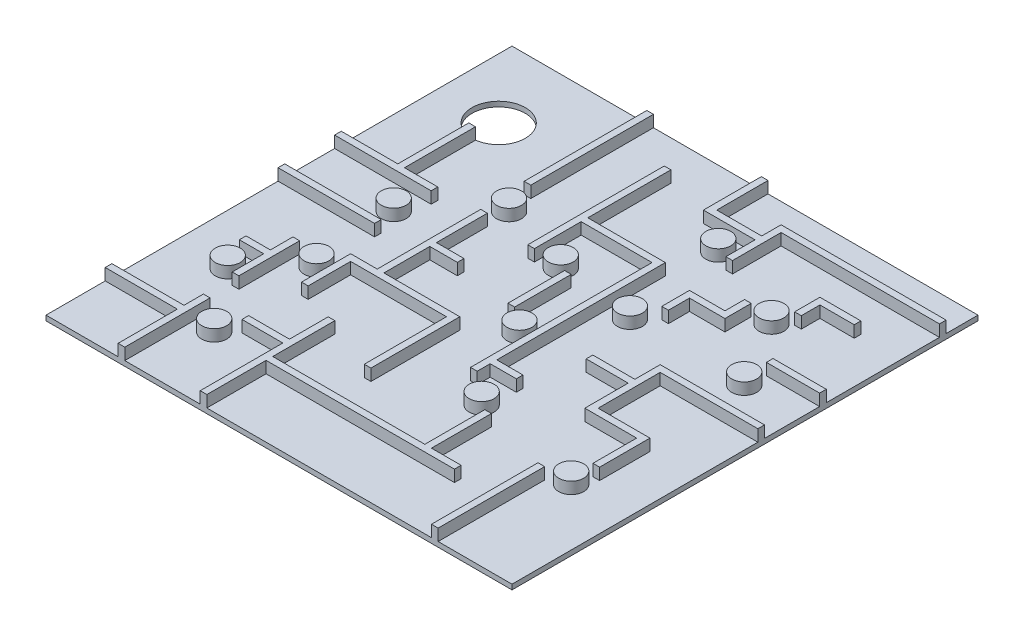
SolidWorks part; units mm, degrees
ref_plane "Front Plane" through (0, 0, 0) normal (0, 0, 1) x (1, 0, 0)
ref_plane "Top Plane" through (0, 0, 0) normal (0, 1, 0) x (1, 0, 0)
ref_plane "Right Plane" through (0, 0, 0) normal (1, 0, 0) x (0, 0, -1)
sketch "Sketch1" plane through (0, 0, 0) normal (0, 1, 0) x (1, 0, 0)
  line L1 (140, -140) -> (-140, -140)
  line L2 (140, -140) -> (140, 140)
  line L3 (140, 140) -> (-140, 140)
  line L4 (-140, -140) -> (-140, 140)
  line L5 (140, -140) -> (-140, 140) construction
  line L6 (140, 140) -> (-140, -140) construction
  circle A0 centre (-104, 96) radius 12.5 construction
  circle A2 centre (-104, 96) radius 16
  point P0 (0, 0)
  dimension "D2" = 25
  dimension "D4" = 36
  dimension "D5" = 44
  dimension "D3" = 32
  dimension "D1" = 280
extrude "Boss-Extrude1" add sketch "Sketch1" along normal mid plane 3
sketch "Sketch2" plane through (0, 1.5, 0) normal (0, 1, 0) x (1, 0, 0)
  line L0 (-139.5466, -22.5168) -> (140.7215, -22.5168) construction
  line L1 (-59, 140) -> (-59, 66.2868)
  line L5 (-140, 140) -> (-140, -140)
  line L6 (-140, -140) -> (140, -140)
  line L7 (140, -140) -> (140, 140)
  line L8 (140, 140) -> (-140, 140)
  line L9 (-140, 140) -> (-140, -140) construction
  line L10 (-140, -140) -> (140, -140) construction
  line L11 (140, -140) -> (140, 140) construction
  line L12 (140, 140) -> (-140, 140) construction
  line L14 (-82, 33.4008) -> (-82, 3.4233) construction
  line L22 (-59, 66.2868) -> (-55, 66.2868)
  line L25 (-55, 66.2868) -> (-55, 140)
  line L26 (-55, 140) -> (-59, 140)
  line L27 (-140, 37.4008) -> (-106, 37.4008)
  line L29 (-106, 37.4008) -> (-106, 80.1255)
  line L31 (-102, 37.4008) -> (-102, 80.1255)
  line L32 (-106, 37.4008) -> (-102, 80.1255) construction
  line L33 (-106, 80.1255) -> (-102, 37.4008) construction
  line L34 (-102, 37.4008) -> (-82, 37.4008)
  line L35 (-82, 37.4008) -> (-82, 33.4008)
  line L36 (-82, 33.4008) -> (-140, 33.4008)
  line L37 (-140, 33.4008) -> (-140, 37.4008)
  line L38 (-140, -100.4184) -> (-96.6685, -100.4184)
  line L39 (-140, 3.4233) -> (-82, 3.4233)
  line L40 (-140, 3.4233) -> (-140, -0.5767)
  line L41 (-140, -0.5767) -> (-82, -0.5767)
  line L42 (-82, 3.4233) -> (-82, -0.5767)
  line L43 (-96.6685, -100.4184) -> (-96.6685, -88.7386)
  line L44 (-96.6685, -88.7386) -> (-92.6685, -88.7386)
  line L45 (-92.6685, -88.7386) -> (-92.6685, -140)
  line L46 (-92.6685, -140) -> (-96.6685, -140)
  line L47 (-96.6685, -140) -> (-96.6685, -104.4184)
  line L48 (-96.6685, -104.4184) -> (-140, -104.4184)
  line L49 (-140, -104.4184) -> (-140, -100.4184)
  line L50 (-47.3451, -140) -> (-47.3451, -90.3646)
  line L51 (-47.3451, -90.3646) -> (-71.8819, -90.3646)
  line L52 (-71.8819, -90.3646) -> (-71.8819, -86.3646)
  line L53 (-71.8819, -86.3646) -> (-47.3451, -86.3646)
  line L54 (-47.3451, -86.3646) -> (-47.3451, -63.0886)
  line L55 (-47.3451, -63.0886) -> (-43.3451, -63.0886)
  line L56 (-43.3451, -63.0886) -> (-43.3451, -100.4184)
  line L57 (-43.3451, -100.4184) -> (48.0278, -100.4184)
  line L58 (48.0278, -100.4184) -> (48.0278, -64.3719)
  line L59 (48.0278, -64.3719) -> (52.0278, -64.3719)
  line L60 (52.0278, -64.3719) -> (52.0278, -100.4184)
  line L61 (52.0278, -100.4184) -> (69.8279, -100.4184)
  line L62 (69.8279, -100.4184) -> (69.8279, -104.4184)
  line L63 (69.8279, -104.4184) -> (-43.3451, -104.4184)
  line L64 (-43.3451, -104.4184) -> (-43.3451, -140)
  line L65 (-43.3451, -140) -> (-47.3451, -140)
  line L66 (140, 7.7373) -> (81.2931, 7.7373)
  line L67 (91.6226, -76) -> (95.6226, -76)
  line L68 (91.6226, -76) -> (91.6226, -140)
  line L69 (91.6226, -140) -> (95.6226, -140)
  line L70 (95.6226, -76) -> (95.6226, -140)
  line L71 (81.2931, 7.7373) -> (81.2931, -29.5435)
  line L72 (81.2931, -29.5435) -> (112.4312, -29.5435)
  line L73 (112.4312, -29.5435) -> (112.4312, -59.7773)
  line L74 (112.4312, -59.7773) -> (108.4312, -59.7773)
  line L75 (108.4312, -59.7773) -> (108.4312, -33.5435)
  line L76 (108.4312, -33.5435) -> (77.2931, -33.5435)
  line L77 (77.2931, -33.5435) -> (77.2931, -7.4768)
  line L78 (77.2931, -7.4768) -> (52.0278, -7.4768)
  line L79 (52.0278, -7.4768) -> (52.0278, -3.4768)
  line L80 (52.0278, -3.4768) -> (77.2931, -3.4768)
  line L81 (77.2931, -3.4768) -> (77.2931, 11.7373)
  line L82 (77.2931, 11.7373) -> (140, 11.7373)
  line L83 (140, 11.7373) -> (140, 7.7373)
  line L84 (-99.5107, -32.1119) -> (-95.5107, -32.1119)
  line L85 (140, 48.844) -> (108, 48.844)
  line L86 (140, 48.844) -> (140, 44.844)
  line L87 (140, 44.844) -> (108, 44.844)
  line L88 (108, 48.844) -> (108, 44.844)
  line L89 (-95.5107, -32.1119) -> (-95.5107, -68.5942)
  line L90 (-95.5107, -68.5942) -> (-99.5107, -68.5942)
  line L91 (-99.5107, -68.5942) -> (-99.5107, -49.6758)
  line L92 (-99.5107, -49.6758) -> (-114.1271, -49.6758)
  line L93 (-114.1271, -49.6758) -> (-114.1271, -45.6758)
  line L94 (-114.1271, -45.6758) -> (-99.5107, -45.6758)
  line L95 (-99.5107, -45.6758) -> (-99.5107, -32.1119)
  line L96 (-73.4352, -53.0425) -> (-69.4352, -53.0425)
  line L97 (-69.4352, -53.0425) -> (-69.4352, -27.5282)
  line L98 (-69.4352, -27.5282) -> (-11.8371, -27.5282)
  line L99 (-11.8371, -27.5282) -> (-11.8371, -76.9197)
  line L100 (-11.8371, -76.9197) -> (-7.8371, -76.9197)
  line L101 (-7.8371, -76.9197) -> (-7.8371, -23.5282)
  line L102 (-7.8371, -23.5282) -> (-53.4401, -23.5282)
  line L103 (-53.4401, -23.5282) -> (-53.4401, 4.0431)
  line L104 (-53.4401, 4.0431) -> (-36.8827, 4.0431)
  line L105 (-36.8827, 4.0431) -> (-36.8827, 8.0431)
  line L106 (-36.8827, 8.0431) -> (-53.4401, 8.0431)
  line L107 (-53.4401, 8.0431) -> (-53.4401, 38.6312)
  line L108 (-53.4401, 38.6312) -> (-57.4401, 38.6312)
  line L109 (-57.4401, 38.6312) -> (-57.4401, -23.5282)
  line L110 (-57.4401, -23.5282) -> (-73.4352, -23.5282)
  line L111 (-73.4352, -23.5282) -> (-73.4352, -53.0425)
  line L112 (114.8331, 94.8013) -> (114.8331, 90.8013)
  line L113 (-0.421, 32.0095) -> (3.579, 32.0095)
  line L114 (-0.421, 32.0095) -> (-0.421, -1.9905)
  line L115 (-0.421, -1.9905) -> (3.579, -1.9905)
  line L116 (3.579, 32.0095) -> (3.579, -1.9905)
  line L117 (114.8331, 90.8013) -> (94.2035, 90.8013)
  line L118 (94.2035, 90.8013) -> (94.2035, 79.6255)
  line L119 (94.2035, 79.6255) -> (90.2035, 79.6255)
  line L120 (90.2035, 79.6255) -> (90.2035, 94.8013)
  line L121 (90.2035, 94.8013) -> (114.8331, 94.8013)
  line L122 (68.7421, 71) -> (68.7421, 59.1986)
  line L123 (68.7421, 59.1986) -> (47.4471, 59.1986)
  line L124 (47.4471, 59.1986) -> (47.4471, 42.5547)
  line L125 (47.4471, 42.5547) -> (51.4471, 42.5547)
  line L126 (51.4471, 42.5547) -> (51.4471, 55.1986)
  line L127 (51.4471, 55.1986) -> (72.7421, 55.1986)
  line L128 (72.7421, 55.1986) -> (72.7421, 71)
  line L129 (72.7421, 71) -> (68.7421, 71)
  line L130 (21.7271, -46.6316) -> (25.7271, -46.6316)
  line L131 (25.7271, -46.6316) -> (25.7271, -38.8445)
  line L132 (25.7271, -38.8445) -> (41.4595, -38.8445)
  line L133 (41.4595, -38.8445) -> (41.4595, -34.8445)
  line L134 (41.4595, -34.8445) -> (25.7271, -34.8445)
  line L135 (25.7271, -34.8445) -> (25.7271, 66.4202)
  line L136 (25.7271, 66.4202) -> (-20.8726, 66.4202)
  line L137 (-20.8726, 66.4202) -> (-20.8726, 116.3442)
  line L138 (-20.8726, 116.3442) -> (-24.8726, 116.3442)
  line L139 (-24.8726, 116.3442) -> (-24.8726, 34.358)
  line L140 (-24.8726, 34.358) -> (-20.8726, 34.358)
  line L141 (-20.8726, 34.358) -> (-20.8726, 62.4202)
  line L142 (-20.8726, 62.4202) -> (21.7271, 62.4202)
  line L143 (21.7271, 62.4202) -> (21.7271, -46.6316)
  line L144 (140, 116.8451) -> (44.8417, 116.8451)
  line L145 (44.8417, 116.8451) -> (44.8417, 87.6566)
  line L146 (44.8417, 87.6566) -> (40.8417, 87.6566)
  line L147 (40.8417, 87.6566) -> (40.8417, 105.182)
  line L148 (40.8417, 105.182) -> (9.8488, 105.182)
  line L149 (9.8488, 105.182) -> (9.8488, 140)
  line L150 (9.8488, 140) -> (13.8488, 140)
  line L151 (13.8488, 140) -> (13.8488, 109.182)
  line L152 (13.8488, 109.182) -> (40.8417, 109.182)
  line L153 (40.8417, 109.182) -> (40.8417, 120.8451)
  line L154 (40.8417, 120.8451) -> (140, 120.8451)
  line L155 (140, 120.8451) -> (140, 116.8451)
  circle A0 centre (-104, 96) radius 16 construction
  circle A1 centre (-104, 96) radius 16 construction
  arc A5 (-102, 80.1255) -> (-106, 80.1255) centre (-104, 96) cw
  circle A6 centre (-54.759, 52.9828) radius 7.5
  circle A7 centre (-89.4735, 18.412) radius 7.5
  circle A8 centre (-83.7389, -33.6905) radius 7.5
  circle A9 centre (-109.5163, -61.2699) radius 7.5
  circle A10 centre (-80.6927, -98.2301) radius 7.5
  circle A12 centre (37.5874, -55.832) radius 7.5
  circle A13 centre (105.9105, -70.3332) radius 7.5
  circle A14 centre (11.8193, -7.3525) radius 7.5
  circle A15 centre (-9.7559, 39.067) radius 7.5
  circle A16 centre (29.1701, 94.8013) radius 7.5
  circle A17 centre (82.6249, 73.2846) radius 7.5
  circle A18 centre (37.5874, 33.2669) radius 7.5
  circle A19 centre (106.2527, 33.2879) radius 7.5
  point P9 (-82, 18.412)
  point P10 (0, 0)
  point P11 (0, 0)
  point P21 (-104, 58.7631)
  point P66 (93.6226, -76)
  dimension "D6" = 29
  dimension "D8" = 15
  dimension "D52" = 15
  dimension "D53" = 15
  dimension "D54" = 15
  dimension "D55" = 15
  dimension "D57" = 15
  dimension "D58" = 15
  dimension "D59" = 15
  dimension "D60" = 15
  dimension "D61" = 15
  dimension "D62" = 15
  dimension "D63" = 15
  dimension "D64" = 15
  dimension "D1" = 0
  dimension "D4" = 4
  dimension "D9" = 4
  dimension "D10" = 4
  dimension "D11" = 58
  dimension "D12" = 4
  dimension "D13" = 58
  dimension "D14" = 4
  dimension "D15" = 4
  dimension "D16" = 4
  dimension "D17" = 4
  dimension "D18" = 4
  dimension "D19" = 4
  dimension "D20" = 4
  dimension "D21" = 4
  dimension "D22" = 64
  dimension "D23" = 4
  dimension "D24" = 4
  dimension "D25" = 4
  dimension "D26" = 4
  dimension "D27" = 4
  dimension "D28" = 4
  dimension "D29" = 32
  dimension "D30" = 4
  dimension "D31" = 4
  dimension "D32" = 4
  dimension "D33" = 4
  dimension "D34" = 4
  dimension "D35" = 4
  dimension "D36" = 4
  dimension "D37" = 4
  dimension "D38" = 34
  dimension "D39" = 4
  dimension "D40" = 4
  dimension "D41" = 4
  dimension "D42" = 4
  dimension "D43" = 4
  dimension "D44" = 4
  dimension "D45" = 4
  dimension "D46" = 4
  dimension "D47" = 4
  dimension "D48" = 4
  dimension "D49" = 4
  dimension "D50" = 4
  dimension "D51" = 4
extrude "Boss-Extrude2" add sketch "Sketch2" along normal blind 7
sketch "Sketch4" plane through (0, 1.5, 0) normal (0, 1, 0) x (1, 0, 0)
  line L0 (-59, 140) -> (-140, 140) construction
  line L1 (-103.2689, 140) -> (-87.6691, 140)
  line L2 (-103.2689, 140) -> (-103.2689, 109.252)
  line L3 (-103.2689, 109.252) -> (-87.6691, 109.252)
  line L4 (-87.6691, 140) -> (-87.6691, 109.252)
  line L5 (5.9631, 143.7406) -> (7.9794, 102.774)
  line L6 (-145.5082, 88.7508) -> (-75.5684, 88.7508)
  line L7 (-145.5082, 88.7508) -> (-145.5082, 30.0852)
  line L8 (-145.5082, 30.0852) -> (-75.5684, 30.0852)
  line L9 (-75.5684, 88.7508) -> (-75.5684, 30.0852)
  line L10 (-62.1484, 143.7406) -> (-36.1488, 143.7406)
  line L11 (-62.1484, 143.7406) -> (-62.1484, 63.1419)
  line L12 (-62.1484, 63.1419) -> (-36.1488, 63.1419)
  line L13 (-36.1488, 143.7406) -> (-36.1488, 63.1419)
  line L14 (-147.4549, 7.7999) -> (-80.2273, 7.7999)
  line L15 (-147.4549, 7.7999) -> (-147.4549, -3.3428)
  line L16 (-147.4549, -3.3428) -> (-80.2273, -3.3428)
  line L17 (-80.2273, 7.7999) -> (-80.2273, -3.3428)
  line L18 (-147.4549, -83.9416) -> (-90.2557, -83.9416)
  line L19 (-147.4549, -83.9416) -> (-147.4549, -144.4835)
  line L20 (-147.4549, -144.4835) -> (-90.2557, -144.4835)
  line L21 (-90.2557, -83.9416) -> (-90.2557, -144.4835)
  line L22 (97.7216, -74.6829) -> (89.8032, -74.6829)
  line L23 (97.7216, -74.6829) -> (97.7216, -144.4835)
  line L24 (97.7216, -144.4835) -> (89.8032, -144.4835)
  line L25 (89.8032, -74.6829) -> (89.8032, -144.4835)
  line L26 (143.8995, -60.5264) -> (51.0585, -60.5264)
  line L27 (143.8995, -60.5264) -> (143.8995, 16.1793)
  line L28 (143.8995, 16.1793) -> (51.0585, 16.1793)
  line L29 (51.0585, -60.5264) -> (51.0585, 16.1793)
  line L30 (88.927, 78.8767) -> (116.5902, 78.8767)
  line L31 (88.927, 78.8767) -> (88.927, 97.3845)
  line L32 (88.927, 97.3845) -> (116.5902, 97.3845)
  line L33 (116.5902, 78.8767) -> (116.5902, 97.3845)
  line L34 (73.3744, 72.1075) -> (45.9857, 72.1075)
  line L35 (73.3744, 72.1075) -> (73.3744, 41.1619)
  line L36 (73.3744, 41.1619) -> (45.9857, 41.1619)
  line L37 (45.9857, 72.1075) -> (45.9857, 41.1619)
  line L38 (105.2092, 50.41) -> (142.3795, 50.41)
  line L39 (105.2092, 50.41) -> (105.2092, 43.6518)
  line L40 (105.2092, 43.6518) -> (142.3795, 43.6518)
  line L41 (142.3795, 50.41) -> (142.3795, 43.6518)
  line L42 (7.9794, 102.774) -> (36.2066, 102.774)
  line L43 (36.2066, 102.774) -> (36.2066, 85.384)
  line L44 (36.2066, 85.384) -> (47.7999, 85.384)
  line L45 (47.7999, 85.384) -> (47.7999, 114.3673)
  line L46 (47.7999, 114.3673) -> (142.3795, 114.3673)
  line L47 (142.3795, 114.3673) -> (142.3795, 146.3749)
  line L48 (142.3795, 146.3749) -> (5.9631, 143.7406)
  line L49 (45.9857, -63.0608) -> (55.6128, -63.0608)
  line L50 (55.6128, -63.0608) -> (55.6128, -94.5644)
  line L51 (55.6128, -94.5644) -> (73.3744, -98.5969)
  line L52 (73.3744, -98.5969) -> (71.3652, -107.4466)
  line L53 (71.3652, -107.4466) -> (-50.2392, -144.4835)
  line L54 (-50.2392, -144.4835) -> (-51.2032, -94.5644)
  line L55 (-51.2032, -94.5644) -> (-74.182, -91.5401)
  line L56 (-74.182, -91.5401) -> (-74.182, -83.9416)
  line L57 (-74.182, -83.9416) -> (-51.2032, -83.9416)
  line L58 (-51.2032, -83.9416) -> (-51.2032, -60.5264)
  line L59 (-51.2032, -60.5264) -> (-41.5994, -61.7904)
  line L60 (-41.5994, -61.7904) -> (-39.8871, -96.5806)
  line L61 (-39.8871, -96.5806) -> (42.0032, -96.5806)
  line L62 (42.0032, -96.5806) -> (45.9857, -63.0608)
  line L63 (-5.6302, -79.1855) -> (-16.4674, -79.1855)
  line L64 (-16.4674, -79.1855) -> (-16.4674, -32.0613)
  line L65 (-16.4674, -32.0613) -> (-66.3537, -32.0613)
  line L66 (-66.3537, -32.0613) -> (-66.3537, -52.7277)
  line L67 (-66.3537, -52.7277) -> (-69.4859, -55.8599)
  line L68 (-69.4859, -55.8599) -> (-74.182, -55.8599)
  line L69 (-74.182, -55.8599) -> (-74.182, -19.9639)
  line L70 (-74.182, -19.9639) -> (-60.8244, -19.9639)
  line L71 (-60.8244, -19.9639) -> (-60.8244, 41.1619)
  line L72 (-60.8244, 41.1619) -> (-50.7212, 41.1619)
  line L73 (-50.7212, 41.1619) -> (-5.6302, -25.2565)
  line L74 (-5.6302, -25.2565) -> (-5.6302, -79.1855)
  line L75 (-95.4557, -29.8902) -> (-93.4806, -70.0213)
  line L76 (-93.4806, -70.0213) -> (-101.149, -70.0213)
  line L77 (-101.149, -70.0213) -> (-101.149, -52.7277)
  line L78 (-101.149, -52.7277) -> (-115.689, -51.0001)
  line L79 (-115.689, -51.0001) -> (-115.689, -42.3945)
  line L80 (-115.689, -42.3945) -> (-103.4173, -42.3945)
  line L81 (-103.4173, -42.3945) -> (-101.9316, -29.8902)
  line L82 (-101.9316, -29.8902) -> (-95.4557, -29.8902)
  line L83 (-28.4925, 119.5346) -> (-16.4674, 117.756)
  line L84 (-1.8935, 32.9846) -> (4.3847, 32.9846)
  line L85 (-1.8935, 32.9846) -> (-1.8935, -2.8259)
  line L86 (-1.8935, -2.8259) -> (4.3847, -2.8259)
  line L87 (4.3847, 32.9846) -> (4.3847, -2.8259)
  line L88 (-16.4674, 117.756) -> (-16.4674, 69.1408)
  line L89 (-16.4674, 69.1408) -> (27.2371, 69.1408)
  line L90 (27.2371, 69.1408) -> (27.2371, -32.0613)
  line L91 (27.2371, -32.0613) -> (45.9857, -32.0613)
  line L92 (45.9857, -32.0613) -> (43.134, -41.9421)
  line L93 (43.134, -41.9421) -> (27.2371, -41.9421)
  line L94 (27.2371, -41.9421) -> (27.2371, -51.0001)
  line L95 (27.2371, -51.0001) -> (17.9746, -49.6302)
  line L96 (17.9746, -49.6302) -> (19.7304, -15.8544)
  line L97 (19.7304, -15.8544) -> (20.3739, 2.1642)
  line L98 (20.3739, 2.1642) -> (18.5332, 38.2959)
  line L99 (18.5332, 38.2959) -> (-16.8954, 50.706)
  line L100 (-16.8954, 50.706) -> (-19.4975, 31.4904)
  line L101 (-19.4975, 31.4904) -> (-28.3046, 32.0909)
  line L102 (-28.3046, 32.0909) -> (-28.4925, 119.5346)
  line L104 (-67.0582, 61.2608) -> (-47.0319, 61.2608)
  line L105 (-67.0582, 61.2608) -> (-67.0582, 43.6518)
  line L106 (-67.0582, 43.6518) -> (-47.0319, 43.6518)
  line L107 (-47.0319, 61.2608) -> (-47.0319, 43.6518)
split "Split2" bodies to split 102 resulting bodies 125 126 127
